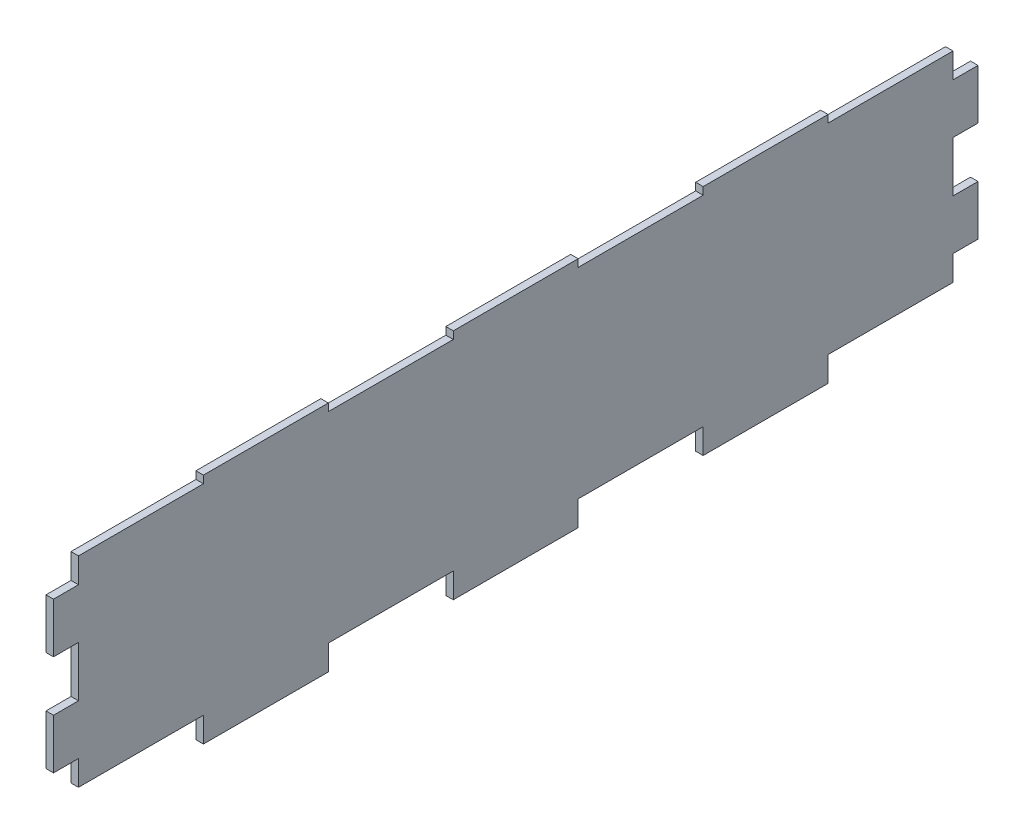
SolidWorks part; units mm, degrees
material "아크릴(내충격성)"
ref_plane "정면" through (0, 0, 0) normal (0, 0, 1) x (1, 0, 0)
ref_plane "윗면" through (0, 0, 0) normal (0, 1, 0) x (1, 0, 0)
ref_plane "우측면" through (0, 0, 0) normal (1, 0, 0) x (0, 0, -1)
sketch "스케치1" plane through (0, 0, 0) normal (1, 0, 0) x (0, 0, -1)
  line L0 (0, 54.3543) -> (0, -46.3467) construction
  line L1 (125, 36.8833) -> (75, 36.8833)
  line L2 (-185, 23.8833) -> (-185, 3.8833)
  line L5 (-175, 36.8833) -> (-175, -56.3467) construction
  line L6 (-185, -46.3467) -> (185, -46.3467) construction
  line L7 (-185, 33.8833) -> (185, 33.8833) construction
  line L8 (-185, -36.3467) -> (-175, -36.3467)
  line L13 (-175, -36.3467) -> (-175, -46.3467)
  line L14 (-185, -16.3467) -> (-175, -16.3467)
  line L15 (-175, -16.3467) -> (-175, 3.8833)
  line L16 (-175, 3.8833) -> (-185, 3.8833)
  line L17 (-185, 23.8833) -> (-175, 23.8833)
  line L18 (-175, 23.8833) -> (-175, 33.8833)
  line L19 (-185, -16.3467) -> (-185, -36.3467)
  line L20 (-125, -56.3467) -> (-75, -56.3467)
  line L21 (175, 36.8833) -> (175, -56.3467) construction
  line L22 (185, -16.3467) -> (185, -36.3467)
  line L23 (175, 23.8833) -> (175, 33.8833)
  line L24 (185, 23.8833) -> (175, 23.8833)
  line L25 (175, 3.8833) -> (185, 3.8833)
  line L26 (175, -16.3467) -> (175, 3.8833)
  line L27 (185, -16.3467) -> (175, -16.3467)
  line L28 (175, -36.3467) -> (175, -46.3467)
  line L29 (185, -36.3467) -> (175, -36.3467)
  line L30 (185, 23.8833) -> (185, 3.8833)
  line L31 (-175, -46.3467) -> (-125, -46.3467)
  line L32 (-125, -46.3467) -> (-125, -56.3467)
  line L33 (-75, -56.3467) -> (-75, -46.3467)
  line L34 (-75, -46.3467) -> (-25, -46.3467)
  line L35 (-25, -46.3467) -> (-25, -56.3467)
  line L36 (25, -46.3467) -> (25, -56.3467)
  line L37 (75, -46.3467) -> (25, -46.3467)
  line L38 (75, -56.3467) -> (75, -46.3467)
  line L39 (125, -46.3467) -> (125, -56.3467)
  line L40 (175, -46.3467) -> (125, -46.3467)
  line L41 (-25, -56.3467) -> (25, -56.3467)
  line L42 (75, -56.3467) -> (125, -56.3467)
  line L43 (-175, 33.8833) -> (-125, 33.8833)
  line L44 (-125, 33.8833) -> (-125, 36.8833)
  line L45 (-75, 36.8833) -> (-75, 33.8833)
  line L46 (-75, 33.8833) -> (-25, 33.8833)
  line L47 (-25, 33.8833) -> (-25, 36.8833)
  line L48 (175, 33.8833) -> (125, 33.8833)
  line L49 (125, 33.8833) -> (125, 36.8833)
  line L50 (75, 36.8833) -> (75, 33.8833)
  line L51 (75, 33.8833) -> (25, 33.8833)
  line L52 (25, 33.8833) -> (25, 36.8833)
  line L53 (-75, 36.8833) -> (-125, 36.8833)
  line L54 (25, 36.8833) -> (-25, 36.8833)
  point P7 (0, 33.8833)
  point P8 (0, -56.3467)
  point P9 (0, 36.8833)
  point P24 (0, -56.3467)
  point P32 (0, 36.8833)
  dimension "D1" = 175
  dimension "D2" = 50
  dimension "D3" = 50
  dimension "D4" = 3
  dimension "D5" = 10
  dimension "D6" = 10
  dimension "D7" = 10
  dimension "D8" = 20
  dimension "D9" = 20
  dimension "D10" = 50
extrude "보스-돌출1" add sketch "스케치1" along normal blind 3
